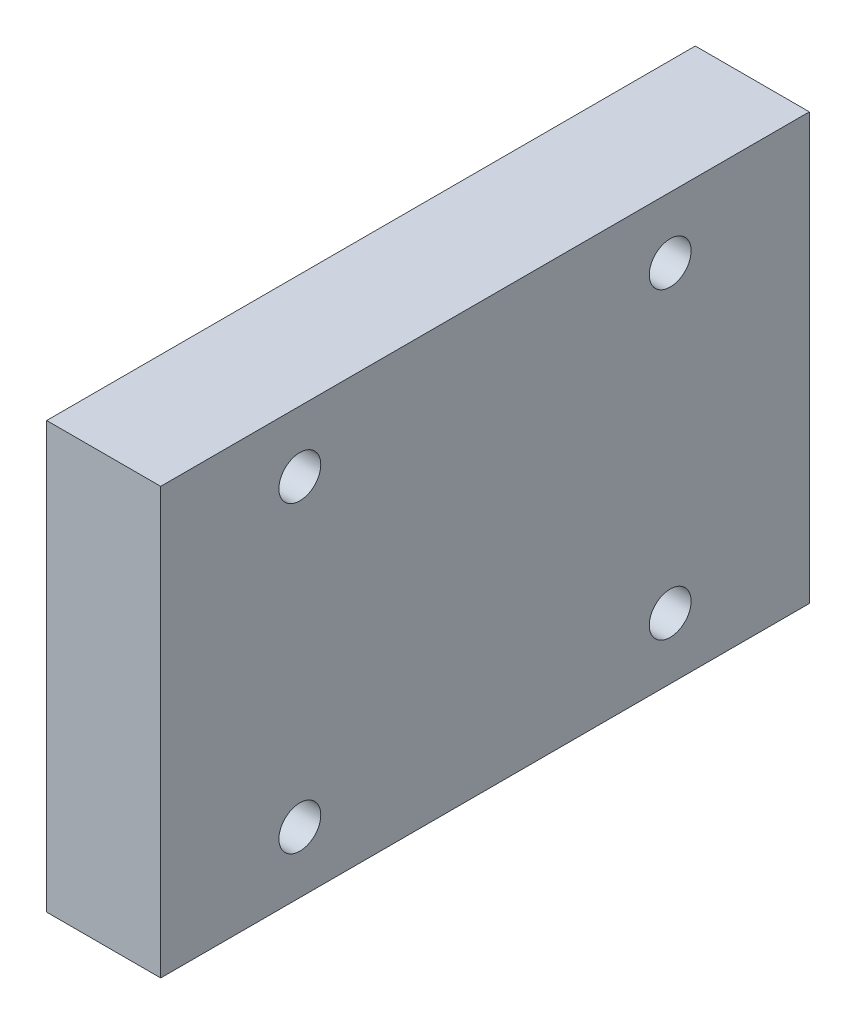
SolidWorks part; units mm, degrees
ref_plane "Front Plane" through (0, 0, 0) normal (0, 0, 1) x (1, 0, 0)
ref_plane "Top Plane" through (0, 0, 0) normal (0, 1, 0) x (1, 0, 0)
ref_plane "Right Plane" through (0, 0, 0) normal (1, 0, 0) x (0, 0, -1)
sketch "Sketch1" plane through (0, 0, 0) normal (1, 0, 0) x (0, 0, -1)
  line L0 (0, 10.175) -> (31, 10.175) construction
  line L1 (0, 0) -> (31, 0)
  line L2 (0, 0) -> (0, 20.35)
  line L3 (0, 20.35) -> (31, 20.35)
  line L4 (31, 0) -> (31, 20.35)
  line L6 (15.5, 20.35) -> (15.5, 0) construction
  circle A0 centre (6.65, 2.925) radius 1
  circle A1 centre (6.65, 17.425) radius 1
  circle A2 centre (24.35, 17.425) radius 1
  circle A3 centre (24.35, 2.925) radius 1
  dimension "D5" = 2
  dimension "D1" = 20.35
  dimension "D2" = 31
  dimension "D3" = 17.7
  dimension "D4" = 14.5
extrude "Boss-Extrude1" add sketch "Sketch1" along normal blind 5.45
